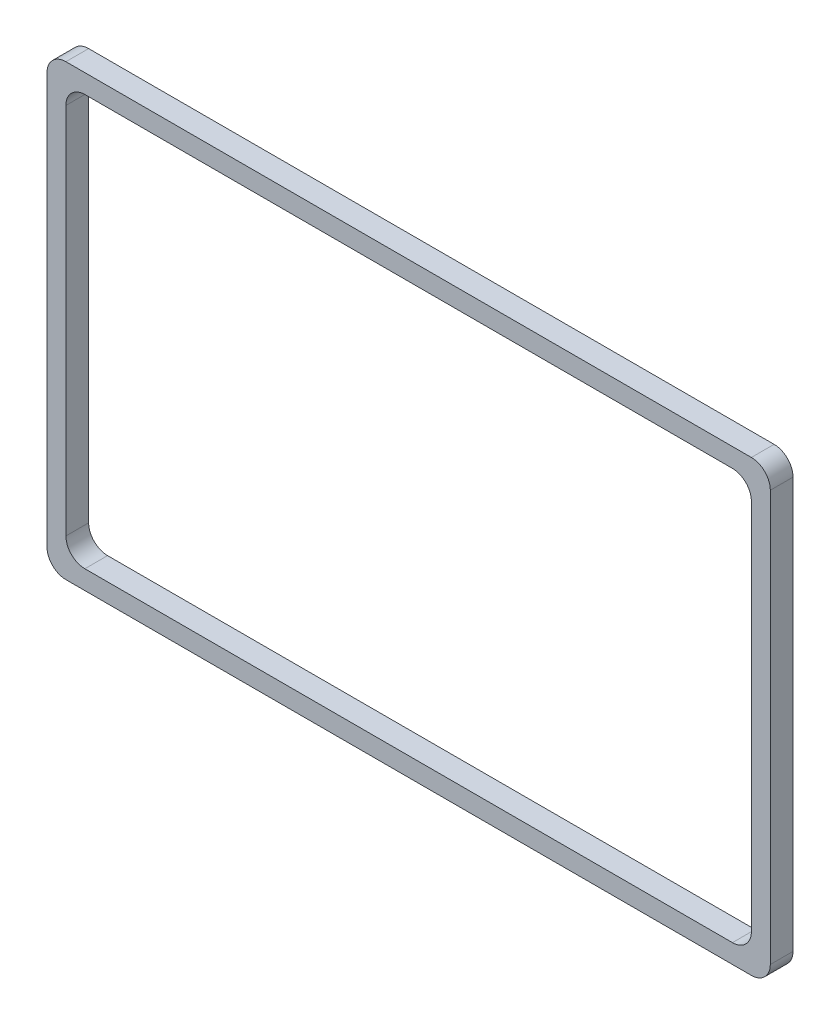
SolidWorks part; units mm, degrees
ref_plane "前视基准面" through (0, 0, 0) normal (0, 0, 1) x (1, 0, 0)
ref_plane "上视基准面" through (0, 0, 0) normal (0, 1, 0) x (1, 0, 0)
ref_plane "右视基准面" through (0, 0, 0) normal (1, 0, 0) x (0, 0, -1)
sketch "草图1" plane through (0, 0, 0) normal (0, 0, 1) x (1, 0, 0)
  line L1 (7.6313, 185.7586) -> (349.6313, 185.7586)
  line L2 (-2.3687, 175.7586) -> (-2.3687, -21.1414)
  line L3 (7.6313, -31.1414) -> (349.6313, -31.1414)
  line L4 (359.6313, 175.7586) -> (359.6313, -21.1414)
  line L5 (-2.3687, 195.7586) -> (359.6313, 195.7586)
  line L6 (-12.3687, 185.7586) -> (-12.3687, -31.1414)
  line L7 (-2.3687, -41.1414) -> (359.6313, -41.1414)
  line L8 (369.6313, 185.7586) -> (369.6313, -31.1414)
  arc A0 (-2.3687, 195.7586) -> (-12.3687, 185.7586) centre (-2.3687, 185.7586) ccw
  arc A1 (-12.3687, -31.1414) -> (-2.3687, -41.1414) centre (-2.3687, -31.1414) ccw
  arc A2 (359.6313, -41.1414) -> (369.6313, -31.1414) centre (359.6313, -31.1414) ccw
  arc A3 (359.6313, 195.7586) -> (369.6313, 185.7586) centre (359.6313, 185.7586) cw
  arc A4 (349.6313, 185.7586) -> (359.6313, 175.7586) centre (349.6313, 175.7586) cw
  arc A5 (349.6313, -31.1414) -> (359.6313, -21.1414) centre (349.6313, -21.1414) ccw
  arc A6 (-2.3687, -21.1414) -> (7.6313, -31.1414) centre (7.6313, -21.1414) ccw
  arc A7 (7.6313, 185.7586) -> (-2.3687, 175.7586) centre (7.6313, 175.7586) ccw
  point P24 (0, 0)
  dimension "D1" = 10
  dimension "D2" = 196.9
  dimension "D3" = 342
  dimension "D4" = 10
  dimension "D5" = 10
  dimension "D6" = 10
  dimension "D7" = 10
extrude "凸台-拉伸1" add sketch "草图1" along normal blind 12
